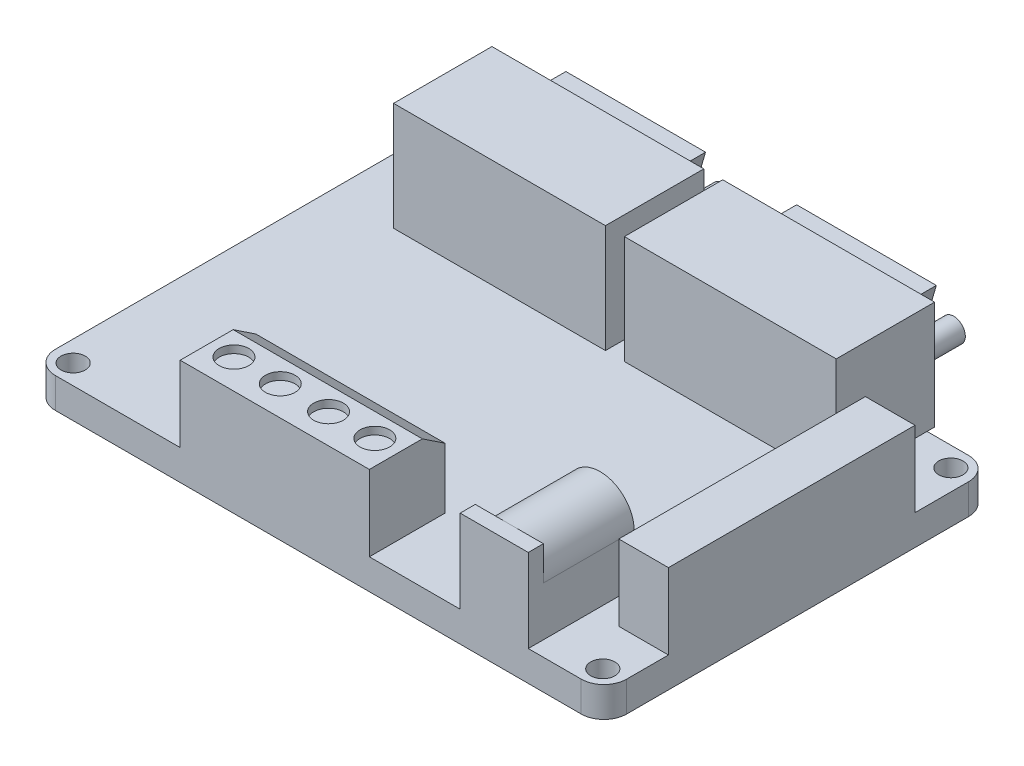
SolidWorks part; units mm, degrees
ref_plane "前视基准面" through (0, 0, 0) normal (0, 0, 1) x (1, 0, 0)
ref_plane "上视基准面" through (0, 0, 0) normal (0, 1, 0) x (1, 0, 0)
ref_plane "右视基准面" through (0, 0, 0) normal (1, 0, 0) x (0, 0, -1)
sketch "草图1" plane through (0, 0, 0) normal (0, 1, 0) x (1, 0, 0)
  line L1 (37.75, -25.6) -> (-37.75, -25.6)
  line L2 (37.75, -25.6) -> (37.75, 25.6)
  line L3 (37.75, 25.6) -> (-37.75, 25.6)
  line L4 (-37.75, -25.6) -> (-37.75, 25.6)
  line L5 (37.75, -25.6) -> (-37.75, 25.6) construction
  line L6 (37.75, 25.6) -> (-37.75, -25.6) construction
  point P0 (0, 0)
  dimension "D1" = 75.5
  dimension "D2" = 51.2
extrude "凸台-拉伸1" add sketch "草图1" along normal blind 4
hole_wizard "M3 间隙孔1" positions "草图2" profile "草图3" hole size "M3" standard "GB" end condition up to next
sketch "草图2" plane through (0, 4, 0) normal (0, 1, 0) x (1, 0, 0)
  line L0 (0, 0) -> (0, 17.2841) construction
  line L2 (0, 0) -> (18.1664, 0) construction
  point P0 (-35, 23)
  point P2 (35, 23)
  point P4 (-35, -23)
  point P6 (35, -23)
  point P15 (0, 0)
  dimension "D1" = 70
  dimension "D2" = 46
sketch "草图3" plane through (-35, 4, -23) normal (1, 0, 0) x (0, 0, 1)
  line L0 (0, 0) -> (0, 4)
  line L1 (0, 4) -> (1.6, 4)
  line L2 (1.6, 4) -> (1.6, 0)
  line L5 (1.6, 0) -> (0, 0)
  line L11 (0, -6.35) -> (0, 107.95) construction
  dimension "通孔孔直径" = 3.2
  dimension "通孔孔深度" = 4
fillet "圆角1" radius 3 4 edges at (-37.75, 2, 25.6) (37.75, 2, 25.6) (37.75, 2, -25.6) (-37.75, 2, -25.6)
sketch "草图4" plane through (0, 0, 25.6) normal (0, 0, 1) x (1, 0, 0)
  line L0 (-34.75, 4) -> (34.75, 4) construction
  line L1 (18.75, 4) -> (27.75, 4)
  line L2 (18.75, 4) -> (18.75, 15)
  line L3 (18.75, 15) -> (27.75, 15)
  line L4 (27.75, 4) -> (27.75, 15)
  line L5 (37.75, 4) -> (37.75, 0) construction
  dimension "D1" = 9
  dimension "D2" = 11
  dimension "D3" = 10
extrude "凸台-拉伸2" add sketch "草图4" against normal blind 14
sketch "草图5" plane through (0, 0, 11.6) normal (0, 0, -1) x (-1, 0, 0)
  line L0 (-27.75, 4) -> (-27.75, 15) construction
  line L1 (-18.75, 15) -> (-18.75, 4) construction
  line L2 (-27.75, 15) -> (-18.75, 15) construction
  line L3 (-27.75, 10.5) -> (-28.75, 10.5)
  line L4 (-28.75, 10.5) -> (-28.75, 16)
  line L5 (-28.75, 16) -> (-17.75, 16)
  line L6 (-17.75, 16) -> (-17.75, 10.5)
  line L7 (-17.75, 10.5) -> (-18.75, 10.5)
  arc A0 (-18.75, 10.5) -> (-27.75, 10.5) centre (-23.25, 10.5) ccw
  dimension "D1" = 1
  dimension "D2" = 1
  dimension "D3" = 1
extrude "切除-拉伸1" cut sketch "草图5" against normal blind 12
sketch "草图6" plane through (0, 4, 0) normal (0, 1, 0) x (1, 0, 0)
  line L0 (-34.75, -25.6) -> (18.75, -25.6) construction
  line L1 (-18.25, -25.6) -> (6.75, -25.6)
  line L2 (-18.25, -25.6) -> (-18.25, -15.6)
  line L3 (-18.25, -15.6) -> (6.75, -15.6)
  line L4 (6.75, -25.6) -> (6.75, -15.6)
  line L5 (18.75, -11.6) -> (18.75, -25.6) construction
  dimension "D1" = 10
  dimension "D2" = 25
  dimension "D3" = 12
extrude "凸台-拉伸3" add sketch "草图6" along normal blind 10
sketch "草图7" plane through (0, 14, 0) normal (0, 1, 0) x (1, 0, 0)
  line L0 (-5.75, -15.6) -> (-5.75, -25.6) construction
  line L1 (6.75, -15.6) -> (-18.25, -15.6) construction
  line L2 (-18.25, -25.6) -> (6.75, -25.6) construction
  line L3 (-5.75, -15.6) -> (-18.25, -15.6) construction
  line L4 (-12, -15.6) -> (-12, -25.6) construction
  circle A0 centre (-15.0598, -21.6845) radius 1.963
  circle A1 centre (-8.9402, -21.6845) radius 1.963
  circle A2 centre (3.5598, -21.6845) radius 1.963
  circle A3 centre (-2.5598, -21.6845) radius 1.963
  point P18 (-15.0598, -21.6845)
extrude "切除-拉伸2" cut sketch "草图7" against normal blind 1
chamfer "倒角1" distance 2 distance2 3 1 edges at (-5.75, 14, 15.6)
sketch "草图8" plane through (0, 4, 0) normal (0, 1, 0) x (1, 0, 0)
  line L0 (37.75, -22.6) -> (37.75, 22.6) construction
  line L1 (37.75, 15.5124) -> (31.1894, 15.5124)
  line L2 (37.75, 15.5124) -> (37.75, -17.076)
  line L3 (37.75, -17.076) -> (31.1894, -17.076)
  line L4 (31.1894, 15.5124) -> (31.1894, -17.076)
extrude "凸台-拉伸4" add sketch "草图8" along normal blind 10
sketch "草图9" plane through (0, 4, 0) normal (0, 1, 0) x (1, 0, 0)
  line L0 (0, 0) -> (0, 35.6203) construction
  line L1 (-29.25, 31.6) -> (-1.25, 31.6)
  line L2 (-29.25, 31.6) -> (-29.25, 13.6)
  line L3 (-29.25, 13.6) -> (-1.25, 13.6)
  line L4 (-1.25, 31.6) -> (-1.25, 13.6)
  line L5 (1.25, 31.6) -> (1.25, 13.6)
  line L6 (29.25, 13.6) -> (1.25, 13.6)
  line L7 (29.25, 31.6) -> (29.25, 13.6)
  line L8 (29.25, 31.6) -> (1.25, 31.6)
  line L9 (34.75, 25.6) -> (-34.75, 25.6) construction
  dimension "D1" = 6
  dimension "D2" = 2.5
  dimension "D3" = 12
  dimension "D4" = 28
extrude "凸台-拉伸5" add sketch "草图9" along normal blind 14.3
sketch "草图10" plane through (0, 0, -31.6) normal (0, 0, -1) x (-1, 0, 0)
  line L0 (-15.25, 18.3) -> (-15.25, 4) construction
  line L1 (-29.25, 18.3) -> (-1.25, 18.3) construction
  line L2 (-29.25, 4) -> (-1.25, 4) construction
  line L3 (-6.0203, 15.3252) -> (-24.4797, 15.3252)
  line L4 (-24.4797, 15.3252) -> (-22.4046, 8.1776)
  line L5 (-6.0203, 15.3252) -> (-8.0954, 8.1776)
  line L6 (-22.4046, 8.1776) -> (-8.0954, 8.1776)
  line L7 (0, 0) -> (0, 21.9538) construction
  line L8 (-29.25, 18.3) -> (-1.25, 18.3)
  line L9 (-29.25, 18.3) -> (-29.25, 4)
  line L10 (-29.25, 4) -> (-1.25, 4)
  line L11 (-1.25, 18.3) -> (-1.25, 4)
  line L12 (-29.25, 18.3) -> (-29.25, 4)
  line L13 (-1.25, 18.3) -> (-1.25, 4)
  line L14 (-24.4797, 15.3252) -> (-22.4046, 8.1776)
  line L15 (-6.0203, 15.3252) -> (-8.0954, 8.1776)
  line L16 (15.25, 18.3) -> (15.25, 4) construction
  line L17 (6.0203, 15.3252) -> (8.0954, 8.1776)
  line L18 (24.4797, 15.3252) -> (22.4046, 8.1776)
  line L19 (1.25, 18.3) -> (1.25, 4)
  line L20 (29.25, 18.3) -> (29.25, 4)
  line L21 (1.25, 18.3) -> (1.25, 4)
  line L22 (29.25, 4) -> (1.25, 4)
  line L23 (29.25, 18.3) -> (29.25, 4)
  line L24 (29.25, 18.3) -> (1.25, 18.3)
  line L25 (22.4046, 8.1776) -> (8.0954, 8.1776)
  line L26 (6.0203, 15.3252) -> (8.0954, 8.1776)
  line L27 (24.4797, 15.3252) -> (22.4046, 8.1776)
  line L28 (6.0203, 15.3252) -> (24.4797, 15.3252)
  circle A0 centre (-26.7699, 11.4091) radius 1.5422
  circle A1 centre (-3.7301, 11.4091) radius 1.5422
  circle A2 centre (-26.7699, 11.4091) radius 1.5422
  circle A3 centre (-3.7301, 11.4091) radius 1.5422
  circle A4 centre (3.7301, 11.4091) radius 1.5422
  circle A5 centre (26.7699, 11.4091) radius 1.5422
  circle A6 centre (3.7301, 11.4091) radius 1.5422
  circle A7 centre (26.7699, 11.4091) radius 1.5422
  point P9 (-15.25, 15.3252)
  point P11 (-15.25, 8.1776)
  point P43 (15.25, 8.1776)
  point P44 (15.25, 15.3252)
  line M2 (-29.25, 4) -> (-1.25, 4)
  line M3 (-1.25, 4) -> (-1.25, 18.3)
  line M4 (-1.25, 18.3) -> (-29.25, 18.3)
  line M5 (-29.25, 18.3) -> (-29.25, 4)
extrude "切除-拉伸3" cut sketch "草图10" against normal blind 5 contours L6 L4 L3 L5 A0 A1 M5 M2 M3 M4 | L20 L24 L19 L22 L17 L28 L18 L25 A4 A5
